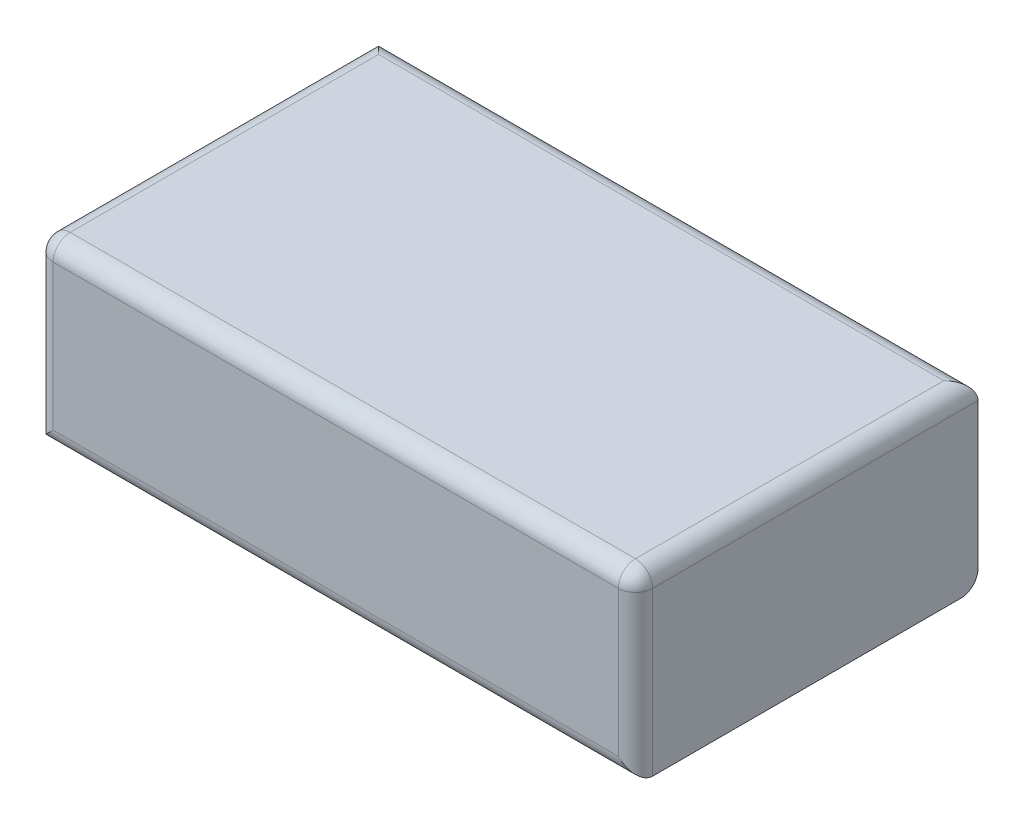
SolidWorks part; units mm, degrees
ref_plane "前视基准面" through (0, 0, 0) normal (0, 0, 1) x (1, 0, 0)
ref_plane "上视基准面" through (0, 0, 0) normal (0, 1, 0) x (1, 0, 0)
ref_plane "右视基准面" through (0, 0, 0) normal (1, 0, 0) x (0, 0, -1)
sketch "草图1" plane through (0, 0, 0) normal (0, 1, 0) x (1, 0, 0)
  line L0 (-17.5, 10) -> (-17.5, -10)
  line L1 (-17.5, -10) -> (17.5, -10)
  line L2 (17.5, -10) -> (17.5, 10)
  line L3 (17.5, 10) -> (-17.5, 10)
  point P7 (0, -5.4882)
  dimension "D1" = 35
  dimension "D2" = 20
  dimension "D3" = 10
  dimension "D4" = 17.5
extrude "凸台-拉伸1" add sketch "草图1" along normal blind 10.5
fillet "圆角1" radius 1 8 edges at (17.5, 10.5, 0) (-17.5, 10.5, 0) (0, 10.5, -10) (-17.5, 5.25, 10) (0, 10.5, 10) (17.5, 5.25, 10) (0, 0, 10) (0, 0, -10)
